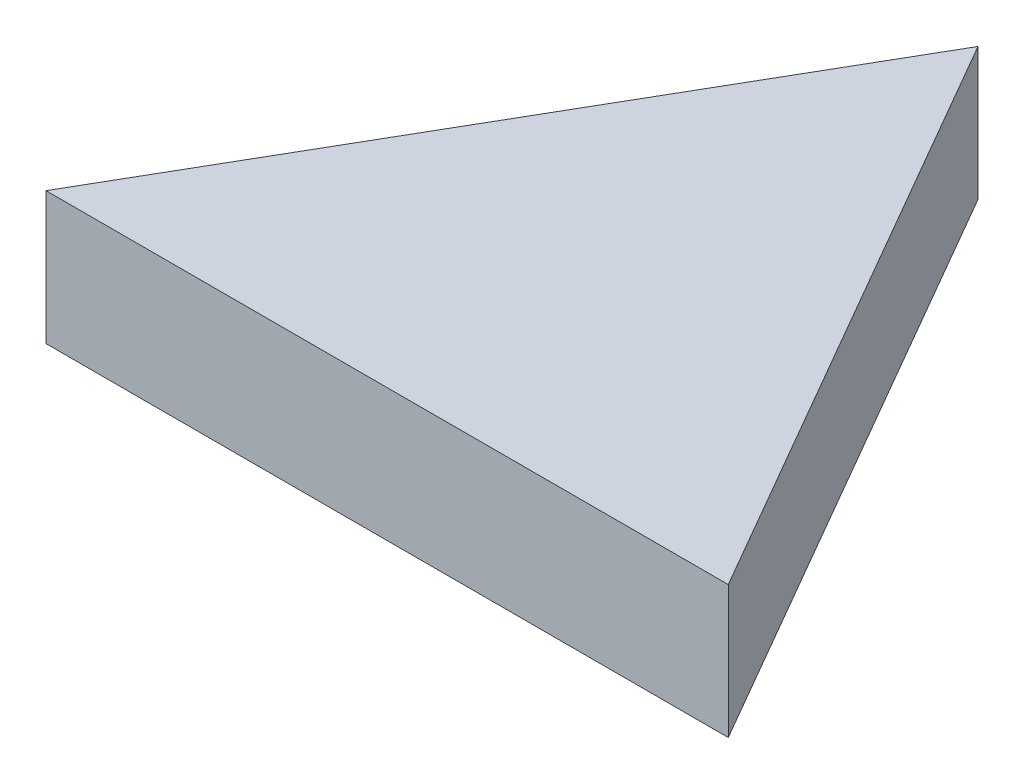
SolidWorks part; units mm, degrees
ref_plane "Front Plane" through (0, 0, 0) normal (0, 0, 1) x (1, 0, 0)
ref_plane "Top Plane" through (0, 0, 0) normal (0, 1, 0) x (1, 0, 0)
ref_plane "Right Plane" through (0, 0, 0) normal (1, 0, 0) x (0, 0, -1)
sketch "Sketch1" plane through (0, 0, 0) normal (0, 1, 0) x (1, 0, 0)
  line L0 (0, 0) -> (1854.06, 0)
  line L1 (1854.06, 0) -> (927.03, 1605.6631)
  line L2 (927.03, 1605.6631) -> (0, 0)
  dimension "D1" = 1854.06
extrude "Boss-Extrude1" add sketch "Sketch1" along normal blind 360
equation "\"D1@Sketch1\"=\"B@Geodome.Assembly\""
equation "\"D1@Boss-Extrude1\"= \"thicknes@Geodome.Assembly\" * 4"
